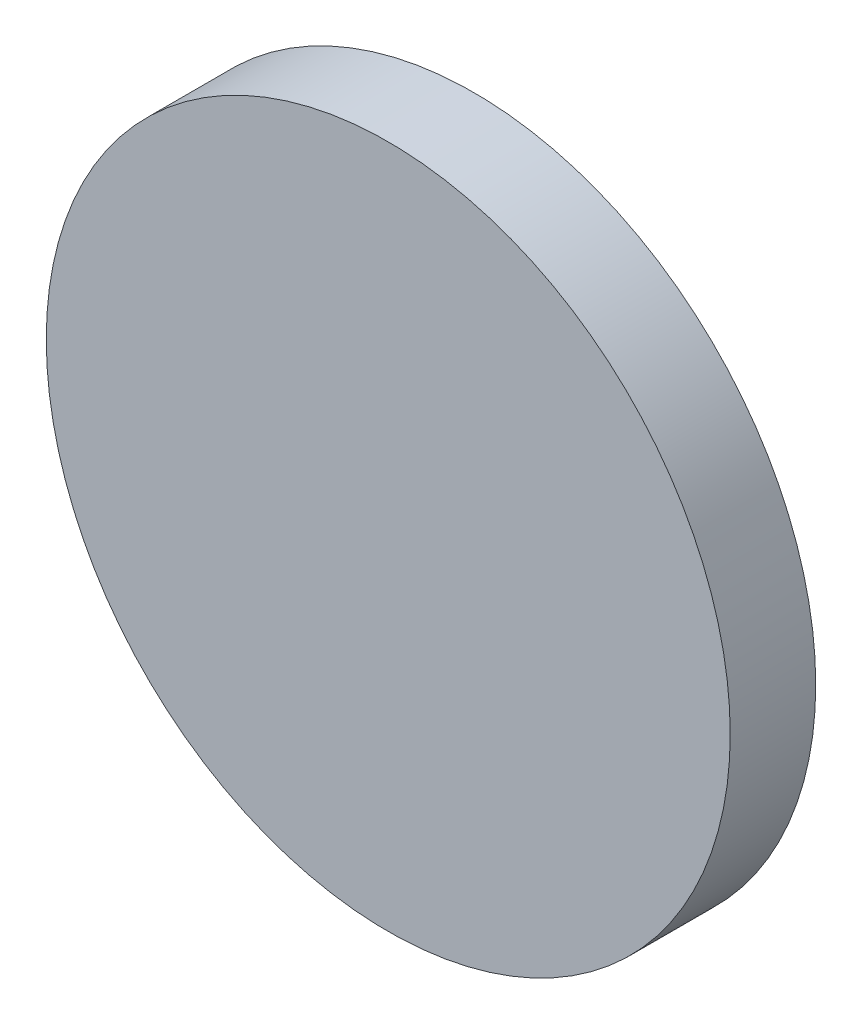
SolidWorks part; units mm, degrees
ref_plane "Front Plane" through (0, 0, 0) normal (0, 0, 1) x (1, 0, 0)
ref_plane "Top Plane" through (0, 0, 0) normal (0, 1, 0) x (1, 0, 0)
ref_plane "Right Plane" through (0, 0, 0) normal (1, 0, 0) x (0, 0, -1)
sketch "Sketch1" plane through (0, 0, 0) normal (0, 0, 1) x (1, 0, 0)
  circle A0 centre (0, 0) radius 12.7
  dimension "D1" = 25.4
extrude "Boss-Extrude1" add sketch "Sketch1" along normal blind 3.175
